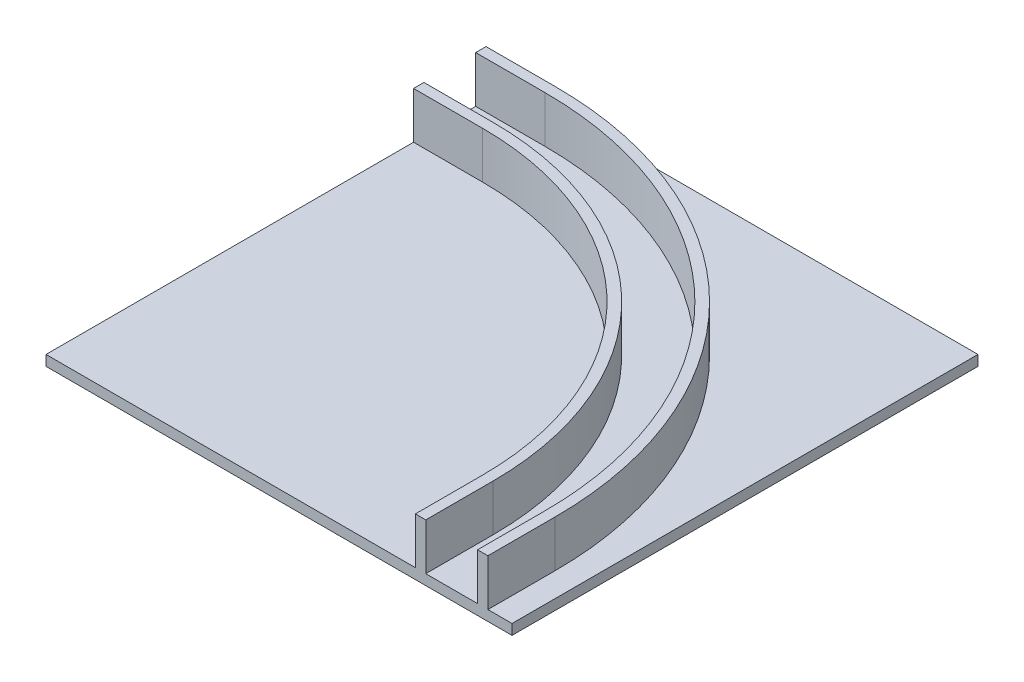
SolidWorks part; units mm, degrees
ref_plane "前视基准面" through (0, 0, 0) normal (0, 0, 1) x (1, 0, 0)
ref_plane "上视基准面" through (0, 0, 0) normal (0, 1, 0) x (1, 0, 0)
ref_plane "右视基准面" through (0, 0, 0) normal (1, 0, 0) x (0, 0, -1)
sketch "草图1" plane through (0, 0, 0) normal (0, 1, 0) x (1, 0, 0)
  line L1 (45, 45) -> (-45, 45)
  line L2 (45, 45) -> (45, -45)
  line L3 (45, -45) -> (-45, -45)
  line L4 (-45, 45) -> (-45, -45)
  line L5 (45, 45) -> (-45, -45) construction
  line L6 (45, -45) -> (-45, 45) construction
  point P0 (0, 0)
  dimension "D1" = 90
  dimension "D2" = 90
extrude "凸台-拉伸1" add sketch "草图1" along normal blind 2
sketch "草图2" plane through (0, 2, 0) normal (0, 1, 0) x (1, 0, 0)
  line L0 (-31.6569, -32.0159) -> (-31.6569, 39.9841) construction
  line L1 (-31.6569, -32.0159) -> (40.3431, -32.0159) construction
  line L14 (-31.6569, 39.9841) -> (-45, 39.9841)
  line L16 (-45, 45) -> (-45, -45) construction
  line L17 (-31.6569, 27.9841) -> (-45, 27.9841)
  line L18 (28.3431, -32.0159) -> (28.3431, -45)
  line L19 (-45, -45) -> (45, -45) construction
  line L20 (40.3431, -32.0159) -> (40.3431, -45)
  arc A0 (28.3431, -32.0159) -> (-31.6569, 27.9841) centre (-31.6569, -32.0159) ccw
  arc A1 (40.3431, -32.0159) -> (-31.6569, 39.9841) centre (-31.6569, -32.0159) ccw
  dimension "D2" = 12
  dimension "D1" = 60
extrude "拉伸-薄壁5" add sketch "草图2" along normal blind 9 thin thin type one direction wall 2
